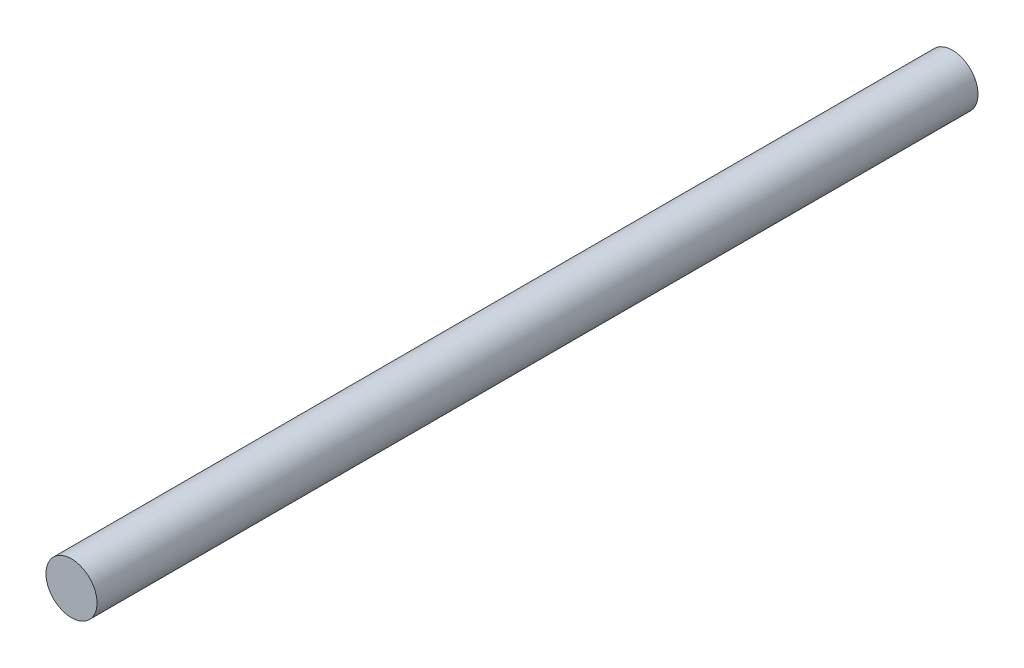
SolidWorks part; units mm, degrees
ref_plane "Front Plane" through (0, 0, 0) normal (0, 0, 1) x (1, 0, 0)
ref_plane "Top Plane" through (0, 0, 0) normal (0, 1, 0) x (1, 0, 0)
ref_plane "Right Plane" through (0, 0, 0) normal (1, 0, 0) x (0, 0, -1)
sketch "Sketch1" plane through (0, 0, 0) normal (0, 0, 1) x (1, 0, 0)
  circle A0 centre (0, 0) radius 4
  dimension "D1" = 8
extrude "Boss-Extrude1" add sketch "Sketch1" along normal blind 138
